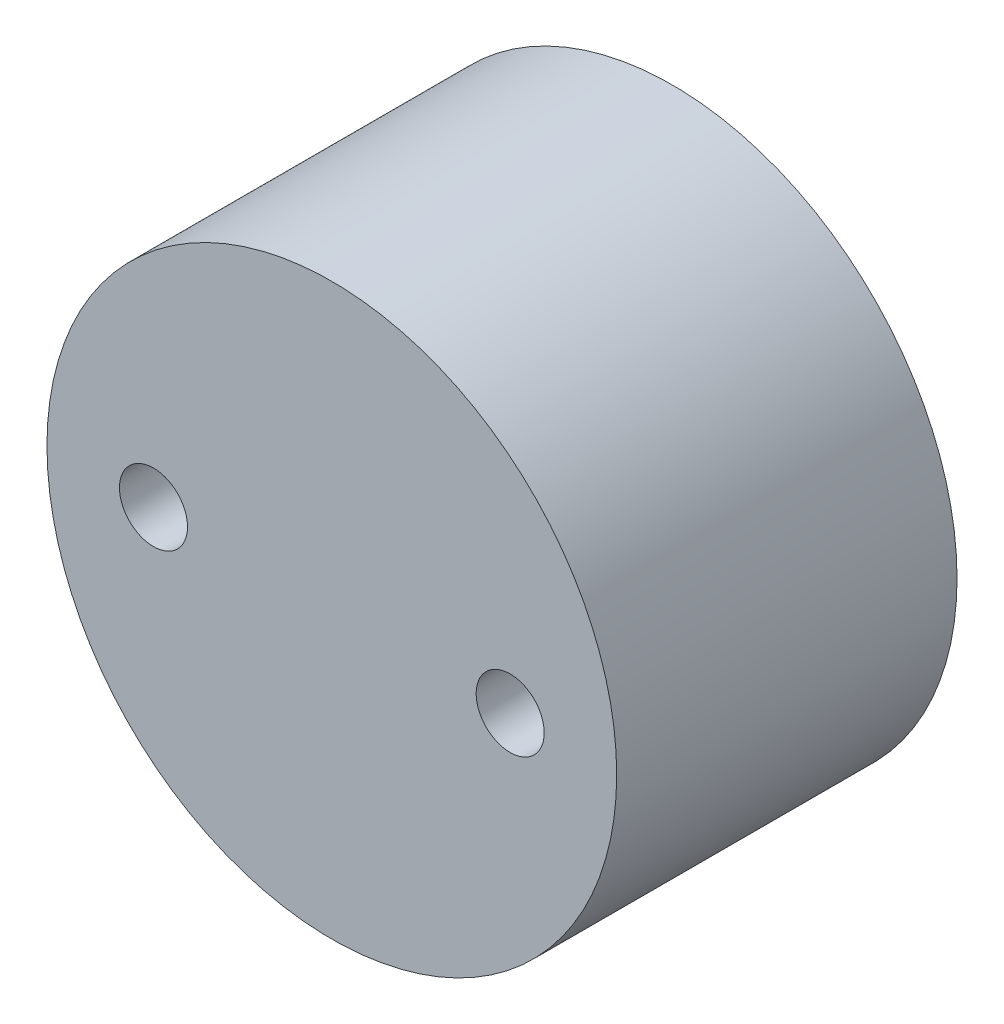
SolidWorks part; units mm, degrees
ref_plane "Front Plane" through (0, 0, 0) normal (0, 0, 1) x (1, 0, 0)
ref_plane "Top Plane" through (0, 0, 0) normal (0, 1, 0) x (1, 0, 0)
ref_plane "Right Plane" through (0, 0, 0) normal (1, 0, 0) x (0, 0, -1)
sketch "Sketch1" plane through (0, 0, 0) normal (0, 0, 1) x (1, 0, 0)
  circle A0 centre (0, 0) radius 4.185
extrude "Boss-Extrude1" add sketch "Sketch1" along normal blind 5
sketch "Sketch2" plane through (0, 0, 5) normal (0, 0, 1) x (1, 0, 0)
  line L0 (0, -55) -> (0, 55) construction
  circle A0 centre (-2.62, 0) radius 0.5
  circle A1 centre (2.62, 0) radius 0.5
  dimension "D2" = 1
  dimension "D1" = 5.24
extrude "Cut-Extrude1" cut sketch "Sketch2" against normal through all
